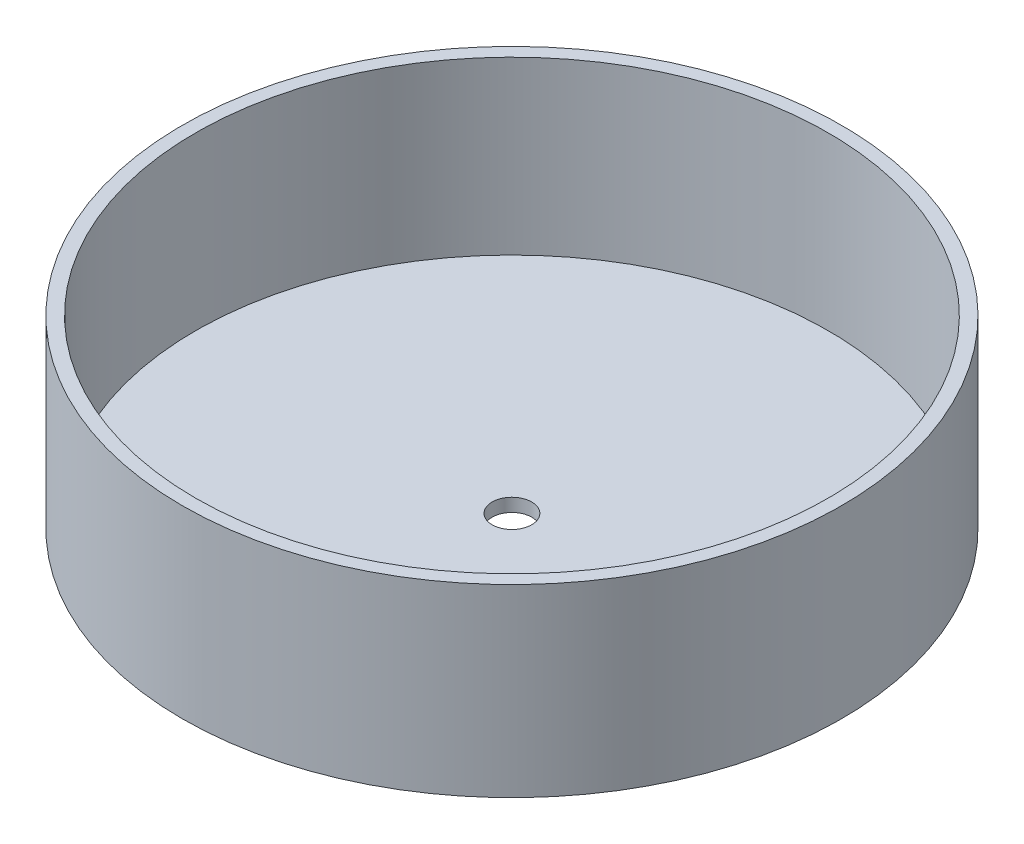
SolidWorks part; units mm, degrees
ref_plane "Front Plane" through (0, 0, 0) normal (0, 0, 1) x (1, 0, 0)
ref_plane "Top Plane" through (0, 0, 0) normal (0, 1, 0) x (1, 0, 0)
ref_plane "Right Plane" through (0, 0, 0) normal (1, 0, 0) x (0, 0, -1)
sketch "Sketch3" plane through (0, 0, 0) normal (0, 1, 0) x (1, 0, 0)
  circle A0 centre (0, 0) radius 125
  dimension "D1" = 250
extrude "Boss-Extrude1" add sketch "Sketch3" along normal mid plane 70
sketch "Sketch4" plane through (0, 35, 0) normal (0, 1, 0) x (1, 0, 0)
  circle A0 centre (0, 0) radius 120
  dimension "D1" = 240
extrude "Cut-Extrude1" cut sketch "Sketch4" against normal blind 65
sketch "Sketch5" plane through (0, -30, 0) normal (0, 1, 0) x (1, 0, 0)
  circle A0 centre (0, 0) radius 7.5
extrude "Cut-Extrude2" cut sketch "Sketch5" against normal through all
